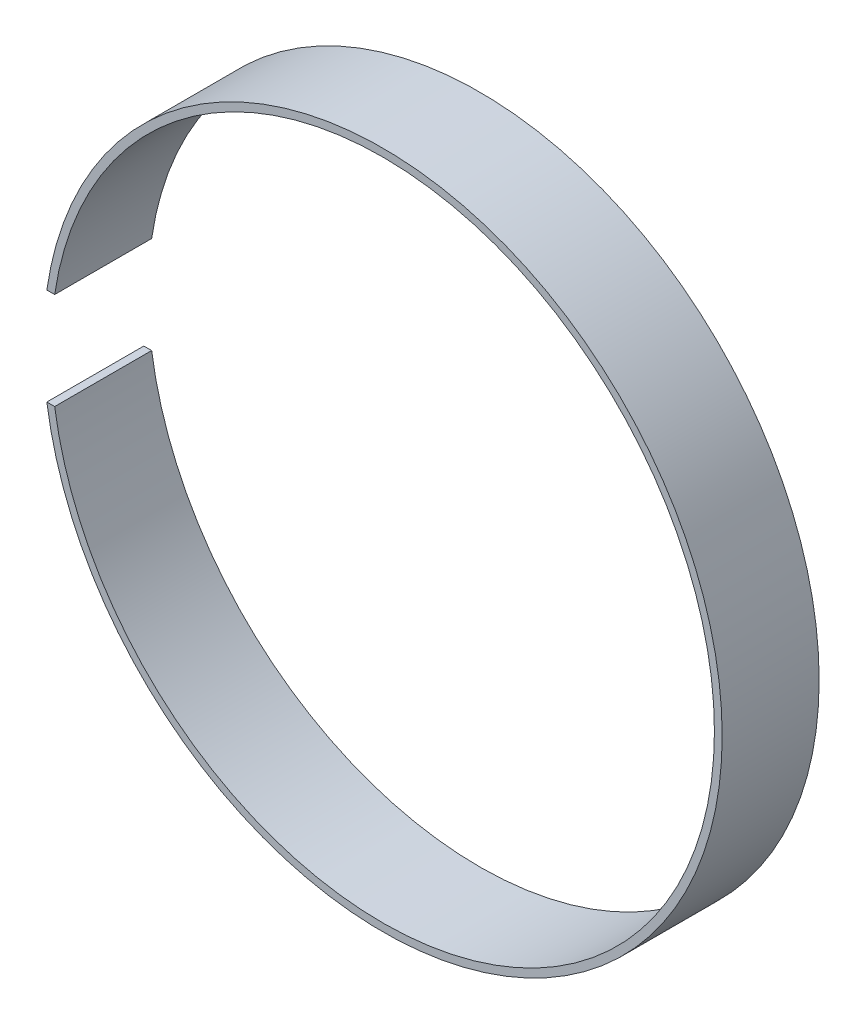
SolidWorks part; units mm, degrees
material "ABS"
ref_plane "Front Plane" through (0, 0, 0) normal (0, 0, 1) x (1, 0, 0)
ref_plane "Top Plane" through (0, 0, 0) normal (0, 1, 0) x (1, 0, 0)
ref_plane "Right Plane" through (0, 0, 0) normal (1, 0, 0) x (0, 0, -1)
sketch "Sketch1" plane through (0, 0, 0) normal (0, 0, 1) x (1, 0, 0)
  line L0 (0, 0) -> (-875, 0) construction
  line L1 (-866.0254, -125) -> (-845.8132, -125)
  line L2 (-866.0254, 125) -> (-845.8132, 125)
  arc A0 (-845.8132, -125) -> (-845.8132, 125) centre (0, 0) ccw
  arc A1 (-866.0254, -125) -> (-866.0254, 125) centre (0, 0) ccw
  circle A2 centre (0, 0) radius 875 construction
  circle A3 centre (0, 0) radius 855 construction
  arc A4 (-866.0254, 125) -> (-875, 0) centre (0, 0) ccw construction
  dimension "D1" = 1710
  dimension "D3" = 125
  dimension "D2" = 20
extrude "Boss-Extrude1" add sketch "Sketch1" along normal blind 250
